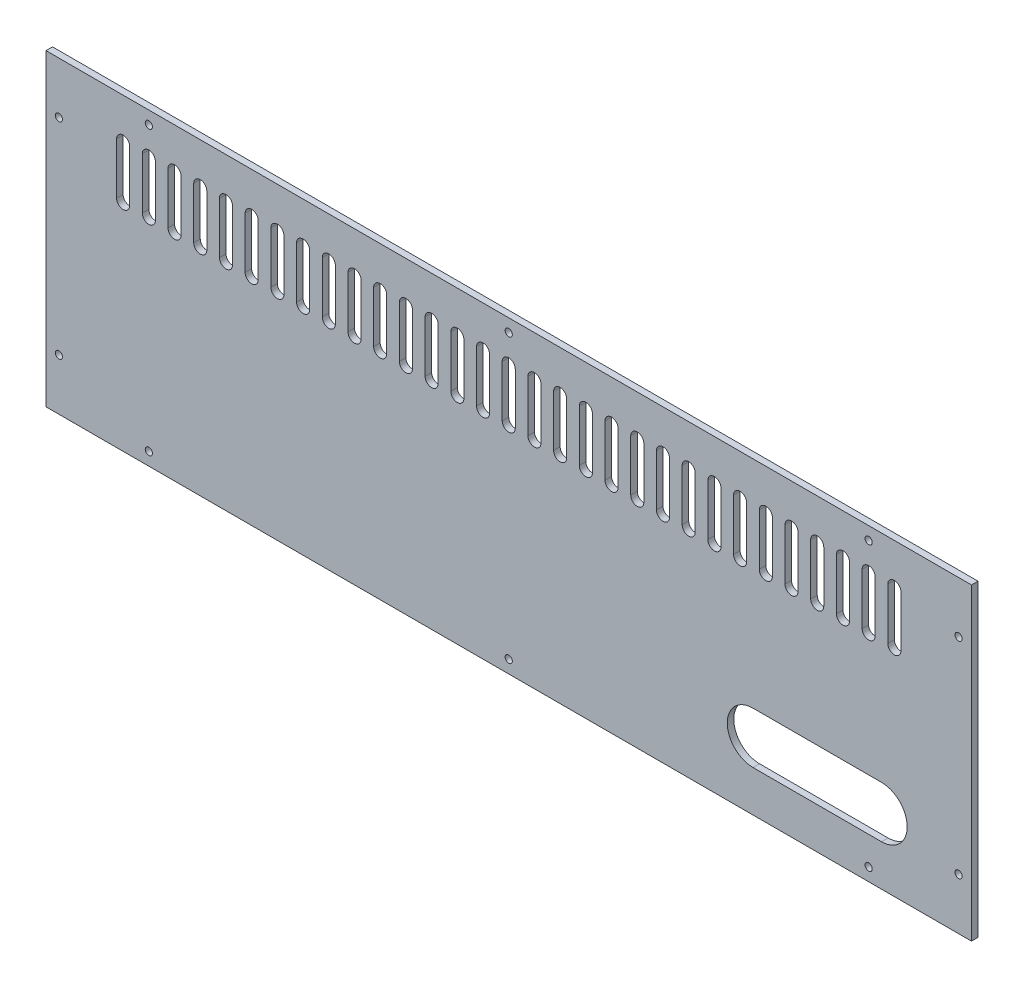
SolidWorks part; units mm, degrees
material "Acrylic (Medium-high impact)"
ref_plane "Front Plane" through (0, 0, 0) normal (0, 0, 1) x (1, 0, 0)
ref_plane "Top Plane" through (0, 0, 0) normal (0, 1, 0) x (1, 0, 0)
ref_plane "Right Plane" through (0, 0, 0) normal (1, 0, 0) x (0, 0, -1)
sketch "Sketch2" plane through (0, 0, 0) normal (0, 0, 1) x (1, 0, 0)
  line L1 (0, 0) -> (900, 0)
  line L2 (0, 0) -> (0, 300)
  line L3 (0, 300) -> (900, 300)
  line L4 (900, 0) -> (900, 300)
  dimension "D1" = 300
  dimension "D2" = 900
extrude "Boss-Extrude1" add sketch "Sketch2" along normal blind 6.35
sketch "Sketch3" plane through (0, 0, 6.35) normal (0, 0, 1) x (1, 0, 0)
  line L0 (450, 300) -> (450, 235) construction
  line L1 (900, 300) -> (0, 300) construction
  line L2 (450, 210) -> (450, 260) construction
  line L3 (443.65, 210) -> (443.65, 260)
  line L4 (456.35, 210) -> (456.35, 260)
  line L5 (481.35, 210) -> (481.35, 260)
  line L6 (468.65, 210) -> (468.65, 260)
  line L7 (475, 210) -> (475, 260) construction
  line L8 (506.35, 210) -> (506.35, 260)
  line L9 (493.65, 210) -> (493.65, 260)
  line L10 (500, 210) -> (500, 260) construction
  line L11 (531.35, 210) -> (531.35, 260)
  line L12 (518.65, 210) -> (518.65, 260)
  line L13 (525, 210) -> (525, 260) construction
  line L14 (556.35, 210) -> (556.35, 260)
  line L15 (543.65, 210) -> (543.65, 260)
  line L16 (550, 210) -> (550, 260) construction
  line L17 (581.35, 210) -> (581.35, 260)
  line L18 (568.65, 210) -> (568.65, 260)
  line L19 (575, 210) -> (575, 260) construction
  line L20 (606.35, 210) -> (606.35, 260)
  line L21 (593.65, 210) -> (593.65, 260)
  line L22 (600, 210) -> (600, 260) construction
  line L23 (631.35, 210) -> (631.35, 260)
  line L24 (618.65, 210) -> (618.65, 260)
  line L25 (625, 210) -> (625, 260) construction
  line L26 (656.35, 210) -> (656.35, 260)
  line L27 (643.65, 210) -> (643.65, 260)
  line L28 (650, 210) -> (650, 260) construction
  line L29 (681.35, 210) -> (681.35, 260)
  line L30 (668.65, 210) -> (668.65, 260)
  line L31 (675, 210) -> (675, 260) construction
  line L32 (706.35, 210) -> (706.35, 260)
  line L33 (693.65, 210) -> (693.65, 260)
  line L34 (700, 210) -> (700, 260) construction
  line L35 (731.35, 210) -> (731.35, 260)
  line L36 (718.65, 210) -> (718.65, 260)
  line L37 (725, 210) -> (725, 260) construction
  line L38 (756.35, 210) -> (756.35, 260)
  line L39 (743.65, 210) -> (743.65, 260)
  line L40 (750, 210) -> (750, 260) construction
  line L41 (781.35, 210) -> (781.35, 260)
  line L42 (768.65, 210) -> (768.65, 260)
  line L43 (775, 210) -> (775, 260) construction
  line L44 (806.35, 210) -> (806.35, 260)
  line L45 (793.65, 210) -> (793.65, 260)
  line L46 (800, 210) -> (800, 260) construction
  line L47 (831.35, 210) -> (831.35, 260)
  line L48 (818.65, 210) -> (818.65, 260)
  line L49 (825, 210) -> (825, 260) construction
  line L50 (456.35, 210) -> (481.35, 210) construction
  line L51 (431.35, 210) -> (431.35, 260)
  line L52 (418.65, 210) -> (418.65, 260)
  line L53 (425, 210) -> (425, 260) construction
  line L54 (406.35, 210) -> (406.35, 260)
  line L55 (393.65, 210) -> (393.65, 260)
  line L56 (400, 210) -> (400, 260) construction
  line L57 (381.35, 210) -> (381.35, 260)
  line L58 (368.65, 210) -> (368.65, 260)
  line L59 (375, 210) -> (375, 260) construction
  line L60 (356.35, 210) -> (356.35, 260)
  line L61 (343.65, 210) -> (343.65, 260)
  line L62 (350, 210) -> (350, 260) construction
  line L63 (331.35, 210) -> (331.35, 260)
  line L64 (318.65, 210) -> (318.65, 260)
  line L65 (325, 210) -> (325, 260) construction
  line L66 (306.35, 210) -> (306.35, 260)
  line L67 (293.65, 210) -> (293.65, 260)
  line L68 (300, 210) -> (300, 260) construction
  line L69 (281.35, 210) -> (281.35, 260)
  line L70 (268.65, 210) -> (268.65, 260)
  line L71 (275, 210) -> (275, 260) construction
  line L72 (256.35, 210) -> (256.35, 260)
  line L73 (243.65, 210) -> (243.65, 260)
  line L74 (250, 210) -> (250, 260) construction
  line L75 (231.35, 210) -> (231.35, 260)
  line L76 (218.65, 210) -> (218.65, 260)
  line L77 (225, 210) -> (225, 260) construction
  line L78 (206.35, 210) -> (206.35, 260)
  line L79 (193.65, 210) -> (193.65, 260)
  line L80 (200, 210) -> (200, 260) construction
  line L81 (181.35, 210) -> (181.35, 260)
  line L82 (168.65, 210) -> (168.65, 260)
  line L83 (175, 210) -> (175, 260) construction
  line L84 (156.35, 210) -> (156.35, 260)
  line L85 (143.65, 210) -> (143.65, 260)
  line L86 (150, 210) -> (150, 260) construction
  line L87 (131.35, 210) -> (131.35, 260)
  line L88 (118.65, 210) -> (118.65, 260)
  line L89 (125, 210) -> (125, 260) construction
  line L90 (106.35, 210) -> (106.35, 260)
  line L91 (93.65, 210) -> (93.65, 260)
  line L92 (100, 210) -> (100, 260) construction
  line L93 (81.35, 210) -> (81.35, 260)
  line L94 (68.65, 210) -> (68.65, 260)
  line L95 (75, 210) -> (75, 260) construction
  line L96 (456.35, 210) -> (431.35, 210) construction
  arc A0 (443.65, 210) -> (456.35, 210) centre (450, 210) ccw
  arc A1 (456.35, 260) -> (443.65, 260) centre (450, 260) ccw
  arc A2 (468.65, 210) -> (481.35, 210) centre (475, 210) ccw
  arc A3 (481.35, 260) -> (468.65, 260) centre (475, 260) ccw
  arc A4 (493.65, 210) -> (506.35, 210) centre (500, 210) ccw
  arc A5 (506.35, 260) -> (493.65, 260) centre (500, 260) ccw
  arc A6 (518.65, 210) -> (531.35, 210) centre (525, 210) ccw
  arc A7 (531.35, 260) -> (518.65, 260) centre (525, 260) ccw
  arc A8 (543.65, 210) -> (556.35, 210) centre (550, 210) ccw
  arc A9 (556.35, 260) -> (543.65, 260) centre (550, 260) ccw
  arc A10 (568.65, 210) -> (581.35, 210) centre (575, 210) ccw
  arc A11 (581.35, 260) -> (568.65, 260) centre (575, 260) ccw
  arc A12 (593.65, 210) -> (606.35, 210) centre (600, 210) ccw
  arc A13 (606.35, 260) -> (593.65, 260) centre (600, 260) ccw
  arc A14 (618.65, 210) -> (631.35, 210) centre (625, 210) ccw
  arc A15 (631.35, 260) -> (618.65, 260) centre (625, 260) ccw
  arc A16 (643.65, 210) -> (656.35, 210) centre (650, 210) ccw
  arc A17 (656.35, 260) -> (643.65, 260) centre (650, 260) ccw
  arc A18 (668.65, 210) -> (681.35, 210) centre (675, 210) ccw
  arc A19 (681.35, 260) -> (668.65, 260) centre (675, 260) ccw
  arc A20 (693.65, 210) -> (706.35, 210) centre (700, 210) ccw
  arc A21 (706.35, 260) -> (693.65, 260) centre (700, 260) ccw
  arc A22 (718.65, 210) -> (731.35, 210) centre (725, 210) ccw
  arc A23 (731.35, 260) -> (718.65, 260) centre (725, 260) ccw
  arc A24 (743.65, 210) -> (756.35, 210) centre (750, 210) ccw
  arc A25 (756.35, 260) -> (743.65, 260) centre (750, 260) ccw
  arc A26 (768.65, 210) -> (781.35, 210) centre (775, 210) ccw
  arc A27 (781.35, 260) -> (768.65, 260) centre (775, 260) ccw
  arc A28 (793.65, 210) -> (806.35, 210) centre (800, 210) ccw
  arc A29 (806.35, 260) -> (793.65, 260) centre (800, 260) ccw
  arc A30 (818.65, 210) -> (831.35, 210) centre (825, 210) ccw
  arc A31 (831.35, 260) -> (818.65, 260) centre (825, 260) ccw
  arc A32 (418.65, 210) -> (431.35, 210) centre (425, 210) ccw
  arc A33 (431.35, 260) -> (418.65, 260) centre (425, 260) ccw
  arc A34 (393.65, 210) -> (406.35, 210) centre (400, 210) ccw
  arc A35 (406.35, 260) -> (393.65, 260) centre (400, 260) ccw
  arc A36 (368.65, 210) -> (381.35, 210) centre (375, 210) ccw
  arc A37 (381.35, 260) -> (368.65, 260) centre (375, 260) ccw
  arc A38 (343.65, 210) -> (356.35, 210) centre (350, 210) ccw
  arc A39 (356.35, 260) -> (343.65, 260) centre (350, 260) ccw
  arc A40 (318.65, 210) -> (331.35, 210) centre (325, 210) ccw
  arc A41 (331.35, 260) -> (318.65, 260) centre (325, 260) ccw
  arc A42 (293.65, 210) -> (306.35, 210) centre (300, 210) ccw
  arc A43 (306.35, 260) -> (293.65, 260) centre (300, 260) ccw
  arc A44 (268.65, 210) -> (281.35, 210) centre (275, 210) ccw
  arc A45 (281.35, 260) -> (268.65, 260) centre (275, 260) ccw
  arc A46 (243.65, 210) -> (256.35, 210) centre (250, 210) ccw
  arc A47 (256.35, 260) -> (243.65, 260) centre (250, 260) ccw
  arc A48 (218.65, 210) -> (231.35, 210) centre (225, 210) ccw
  arc A49 (231.35, 260) -> (218.65, 260) centre (225, 260) ccw
  arc A50 (193.65, 210) -> (206.35, 210) centre (200, 210) ccw
  arc A51 (206.35, 260) -> (193.65, 260) centre (200, 260) ccw
  arc A52 (168.65, 210) -> (181.35, 210) centre (175, 210) ccw
  arc A53 (181.35, 260) -> (168.65, 260) centre (175, 260) ccw
  arc A54 (143.65, 210) -> (156.35, 210) centre (150, 210) ccw
  arc A55 (156.35, 260) -> (143.65, 260) centre (150, 260) ccw
  arc A56 (118.65, 210) -> (131.35, 210) centre (125, 210) ccw
  arc A57 (131.35, 260) -> (118.65, 260) centre (125, 260) ccw
  arc A58 (93.65, 210) -> (106.35, 210) centre (100, 210) ccw
  arc A59 (106.35, 260) -> (93.65, 260) centre (100, 260) ccw
  arc A60 (68.65, 210) -> (81.35, 210) centre (75, 210) ccw
  arc A61 (81.35, 260) -> (68.65, 260) centre (75, 260) ccw
  point P6 (450, 235)
  point P14 (475, 235)
  point P21 (500, 235)
  point P28 (525, 235)
  point P35 (550, 235)
  point P42 (575, 235)
  point P49 (600, 235)
  point P56 (625, 235)
  point P63 (650, 235)
  point P70 (675, 235)
  point P77 (700, 235)
  point P84 (725, 235)
  point P91 (750, 235)
  point P98 (775, 235)
  point P105 (800, 235)
  point P112 (825, 235)
  point P121 (425, 235)
  point P128 (400, 235)
  point P135 (375, 235)
  point P142 (350, 235)
  point P149 (325, 235)
  point P156 (300, 235)
  point P163 (275, 235)
  point P170 (250, 235)
  point P177 (225, 235)
  point P184 (200, 235)
  point P191 (175, 235)
  point P198 (150, 235)
  point P205 (125, 235)
  point P212 (100, 235)
  point P219 (75, 235)
  dimension "D3" = 6.35
  dimension "D1" = 65
  dimension "D2" = 25
  dimension "D5" = 25
  dimension "D7" = 25
  dimension "D4" = 16
  dimension "D6" = 16
extrude "Cut-Extrude1" cut sketch "Sketch3" against normal up to surface (6.35 mm away) up to face at (450, 150, 0)
ref_plane "Plane1" through (0, 150, 0) normal (0, 1, 0) x (1, 0, 0)
ref_plane "Plane2" through (450, 0, 0) normal (-1, 0, 0) x (0, 0, 1)
sketch "Sketch4" plane through (0, 0, 6.35) normal (0, 0, 1) x (1, 0, 0)
  line L0 (0, 150) -> (12.5, 150) construction
  line L1 (0, 300) -> (0, 0) construction
  line L2 (12.5, 150) -> (12.5, 50) construction
  line L3 (12.5, 150) -> (12.5, 250) construction
  line L4 (450, 300) -> (450, 287.5) construction
  line L5 (900, 300) -> (0, 300) construction
  line L6 (450, 287.5) -> (625, 287.5) construction
  line L7 (450, 287.5) -> (275, 287.5) construction
  line L8 (450, 3.4925) -> (450, -3.4925) construction
  line L9 (3.4925, 150) -> (-3.4925, 150) construction
  circle A0 centre (12.5, 150) radius 3.5 construction
  circle A1 centre (12.5, 50) radius 3.5
  circle A2 centre (12.5, 250) radius 3.5
  circle A3 centre (450, 287.5) radius 3.5
  circle A4 centre (625, 287.5) radius 3.5 construction
  circle A5 centre (800, 287.5) radius 3.5
  circle A6 centre (275, 287.5) radius 3.5 construction
  circle A7 centre (100, 287.5) radius 3.5
  circle A8 centre (887.5, 50) radius 3.5
  circle A9 centre (887.5, 150) radius 3.5 construction
  circle A10 centre (887.5, 250) radius 3.5
  circle A11 centre (800, 12.5) radius 3.5
  circle A12 centre (625, 12.5) radius 3.5 construction
  circle A13 centre (450, 12.5) radius 3.5
  circle A14 centre (275, 12.5) radius 3.5 construction
  circle A15 centre (100, 12.5) radius 3.5
  dimension "D2" = 7
  dimension "D8" = 7
  dimension "D1" = 12.5
  dimension "D4" = 100
  dimension "D6" = 100
  dimension "D7" = 12.5
  dimension "D10" = 175
  dimension "D12" = 175
  dimension "D3" = 2
  dimension "D5" = 2
  dimension "D9" = 3
  dimension "D11" = 3
extrude "Cut-Extrude2" cut sketch "Sketch4" against normal through all
sketch "Sketch5" plane through (0, 0, 0) normal (0, 0, -1) x (-1, 0, 0)
  line L0 (-900, 0) -> (-750, 0) construction
  line L1 (0, 0) -> (-900, 0) construction
  line L2 (-750, 0) -> (-750, 65) construction
  line L3 (-812.5, 65) -> (-687.5, 65) construction
  line L4 (-812.5, 90) -> (-687.5, 90)
  line L5 (-812.5, 40) -> (-687.5, 40)
  arc A0 (-812.5, 90) -> (-812.5, 40) centre (-812.5, 65) ccw
  arc A1 (-687.5, 40) -> (-687.5, 90) centre (-687.5, 65) ccw
  point P8 (-750, 65)
  dimension "D3" = 25
  dimension "D1" = 150
  dimension "D2" = 65
  dimension "D4" = 125
extrude "Cut-Extrude3" cut sketch "Sketch5" against normal blind 10
